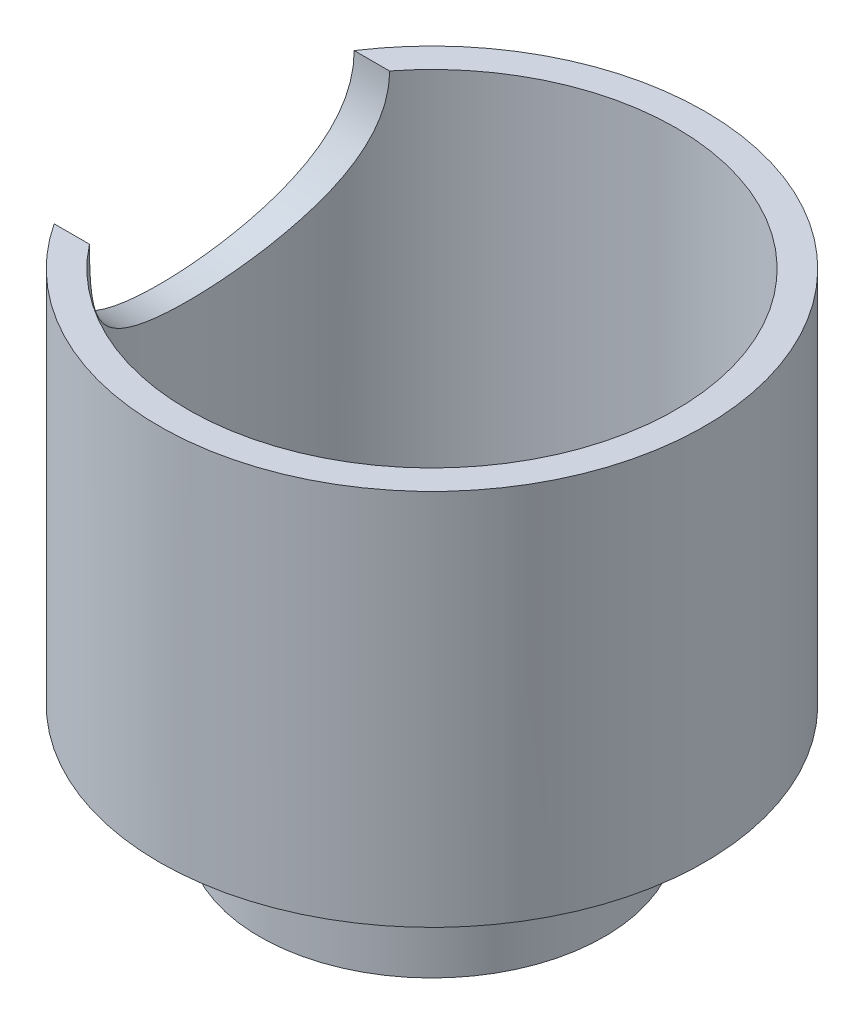
SolidWorks part; units mm, degrees
ref_plane "Front Plane" through (0, 0, 0) normal (0, 0, 1) x (1, 0, 0)
ref_plane "Top Plane" through (0, 0, 0) normal (0, 1, 0) x (1, 0, 0)
ref_plane "Right Plane" through (0, 0, 0) normal (1, 0, 0) x (0, 0, -1)
sketch "Sketch2" plane through (0, 0, 0) normal (0, 0, 1) x (1, 0, 0)
  line L0 (0, 0) -> (0, 19.2692) construction
  line L1 (0, 0) -> (10, 0) construction
  line L2 (10, 0) -> (10, 10)
  line L3 (10, 10) -> (17, 10)
  line L4 (17, 10) -> (17, 34.3)
  line L5 (17, 34.3) -> (19, 34.3)
  line L6 (19, 34.3) -> (19, 8)
  line L7 (19, 8) -> (12, 8)
  line L8 (12, 8) -> (12, 0)
  line L9 (12, 0) -> (10, 0)
  dimension "D1" = 2
  dimension "D2" = 2
  dimension "D3" = 10
  dimension "D4" = 34.3
  dimension "D5" = 17
revolve "Revolve1" add sketch "Sketch2" angle 360 about L0
sketch "Sketch3" plane through (0, 0, 0) normal (1, 0, 0) x (0, 0, -1)
  line L0 (17, 34.3) -> (-17, 34.3) construction
  line L1 (17, 34.3) -> (-17, 34.3) construction
  circle A0 centre (0, 34.3) radius 10.45
  dimension "D1" = 20.9
extrude "Cut-Extrude1" cut sketch "Sketch3" against normal through all
